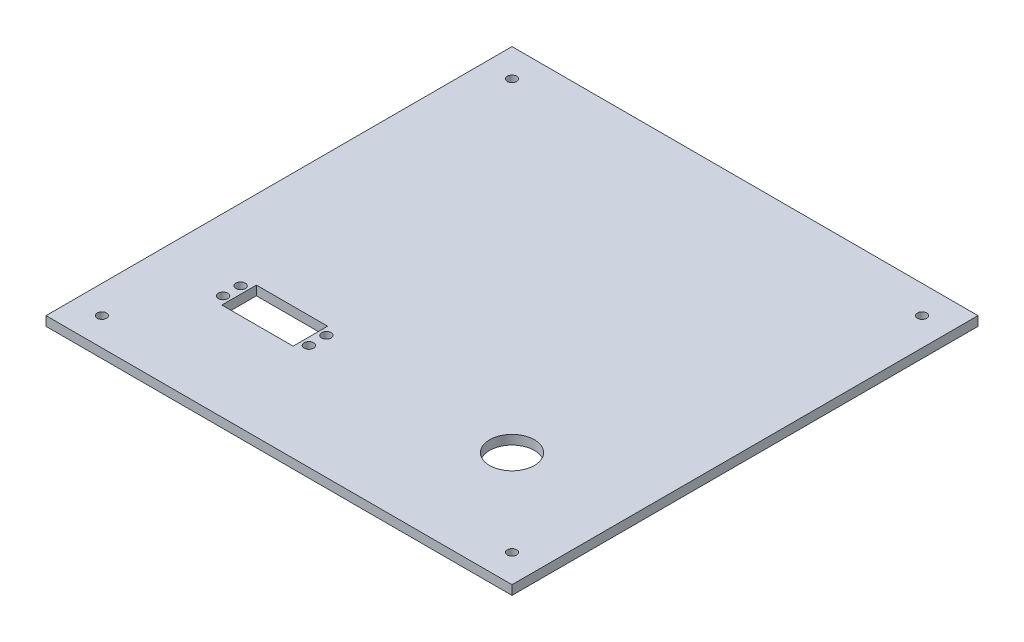
SolidWorks part; units mm, degrees
material "Lega 1060"
ref_plane "Piano frontale" through (0, 0, 0) normal (0, 0, 1) x (1, 0, 0)
ref_plane "Piano superiore" through (0, 0, 0) normal (0, 1, 0) x (1, 0, 0)
ref_plane "Piano destro" through (0, 0, 0) normal (1, 0, 0) x (0, 0, -1)
sketch "Schizzo1" plane through (0, 0, 0) normal (0, 1, 0) x (1, 0, 0)
  line L1 (125, -125) -> (-125, -125)
  line L2 (125, -125) -> (125, 125)
  line L3 (125, 125) -> (-125, 125)
  line L4 (-125, -125) -> (-125, 125)
  line L5 (125, -125) -> (-125, 125) construction
  line L6 (125, 125) -> (-125, -125) construction
  line L7 (110, -110) -> (-110, -110) construction
  line L8 (110, -110) -> (110, 110) construction
  line L9 (110, 110) -> (-110, 110) construction
  line L10 (-110, -110) -> (-110, 110) construction
  line L11 (110, -110) -> (-110, 110) construction
  line L12 (110, 110) -> (-110, -110) construction
  line L13 (-82.7546, -54.3696) -> (-44.5246, -54.3696)
  line L14 (-82.7546, -54.3696) -> (-82.7546, -72.9096)
  line L15 (-82.7546, -72.9096) -> (-44.5246, -72.9096)
  line L16 (-44.5246, -54.3696) -> (-44.5246, -72.9096)
  line L17 (-82.7546, -54.3696) -> (-44.5246, -72.9096) construction
  line L18 (-82.7546, -72.9096) -> (-44.5246, -54.3696) construction
  circle A0 centre (-110, 110) radius 2.5
  circle A1 centre (110, 110) radius 2.5
  circle A2 centre (-110, -110) radius 2.5
  circle A3 centre (110, -110) radius 2.5
  circle A4 centre (63.6396, -63.6396) radius 12
  circle A5 centre (-86.6551, -58.9396) radius 2.54
  circle A6 centre (-86.6551, -68.3376) radius 2.54
  circle A7 centre (-40.6211, -68.3376) radius 2.54
  circle A8 centre (-40.6211, -58.9396) radius 2.54
  point P0 (0, 0)
  point P6 (0, 0)
  point P17 (-63.6396, -63.6396)
  dimension "D3" = 5
  dimension "D4" = 24
  dimension "D1" = 250
  dimension "D2" = 220
  dimension "D5" = 90
  dimension "D6" = 18.54
  dimension "D7" = 38.23
extrude "Estrusione-Estrusione1" add sketch "Schizzo1" along normal blind 5
